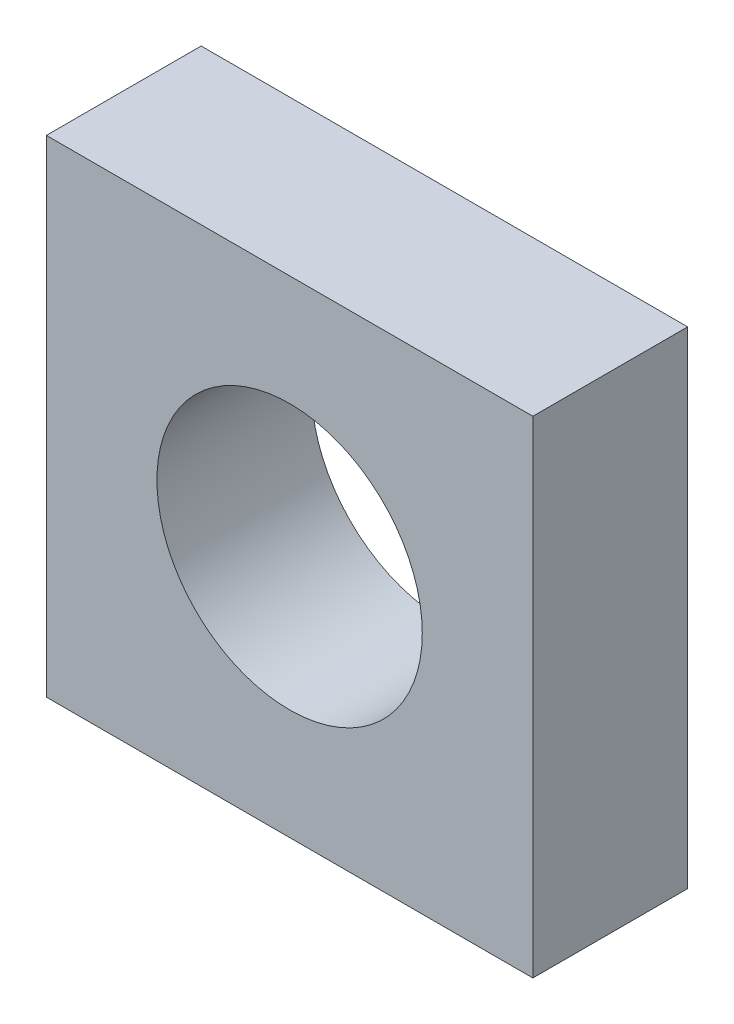
SolidWorks part; units mm, degrees
ref_plane "Front Plane" through (0, 0, 0) normal (0, 0, 1) x (1, 0, 0)
ref_plane "Top Plane" through (0, 0, 0) normal (0, 1, 0) x (1, 0, 0)
ref_plane "Right Plane" through (0, 0, 0) normal (1, 0, 0) x (0, 0, -1)
sketch "Sketch1" plane through (0, 0, 0) normal (0, 0, 1) x (1, 0, 0)
  line L0 (0, 5.5) -> (5.5, 0) construction
  line L1 (0, 0) -> (5.5, 0)
  line L2 (0, 0) -> (0, 5.5)
  line L3 (0, 5.5) -> (5.5, 5.5)
  line L4 (5.5, 0) -> (5.5, 5.5)
  circle A0 centre (2.75, 2.75) radius 1.5
  dimension "D3" = 3
  dimension "D1" = 5.5
  dimension "D2" = 5.5
extrude "Boss-Extrude1" add sketch "Sketch1" along normal blind 1.75
